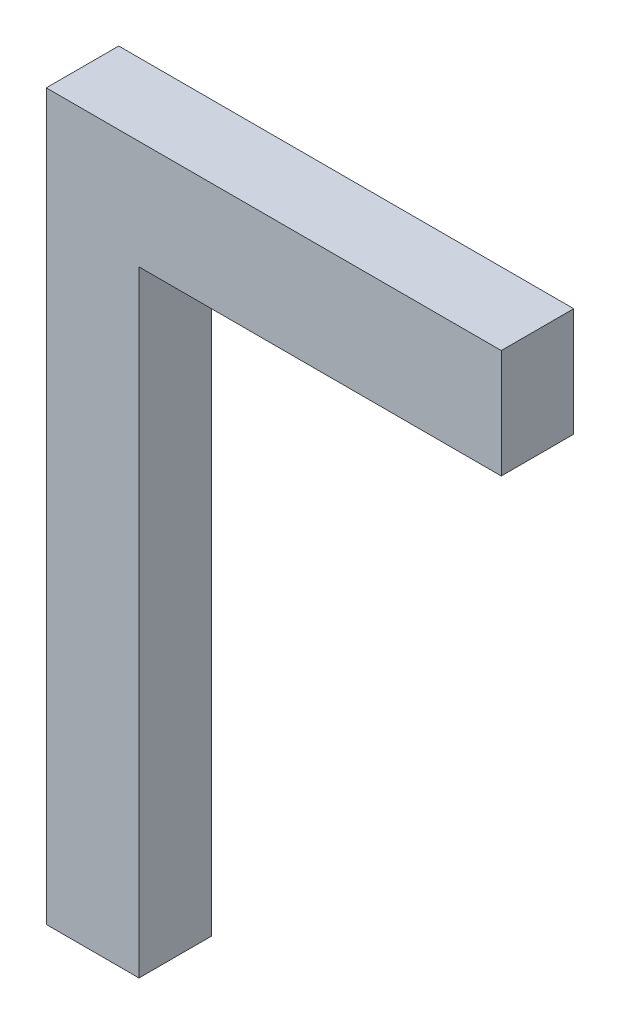
SolidWorks part; units mm, degrees
ref_plane "Front Plane" through (0, 0, 0) normal (0, 0, 1) x (1, 0, 0)
ref_plane "Top Plane" through (0, 0, 0) normal (0, 1, 0) x (1, 0, 0)
ref_plane "Right Plane" through (0, 0, 0) normal (1, 0, 0) x (0, 0, -1)
sketch "Sketch2" plane through (0, 0, 0) normal (0, 1, 0) x (1, 0, 0)
  line L1 (64, -50) -> (-64, -50)
  line L2 (64, -50) -> (64, 50)
  line L3 (64, 50) -> (-64, 50)
  line L4 (-64, -50) -> (-64, 50)
  line L5 (64, -50) -> (-64, 50) construction
  line L6 (64, 50) -> (-64, -50) construction
  point P0 (0, 0)
extrude "Boss-Extrude1" add sketch "Sketch2" along normal blind 1000
sketch "Sketch3" plane through (64, 0, 0) normal (1, 0, 0) x (0, 0, -1)
  line L0 (-50, 1000) -> (-50, 0) construction
  line L1 (50, 1000) -> (-50, 1000)
  line L2 (50, 1000) -> (50, 850)
  line L3 (50, 850) -> (-50, 850)
  line L4 (-50, 1000) -> (-50, 850)
extrude "Boss-Extrude2" add sketch "Sketch3" along normal blind 500
